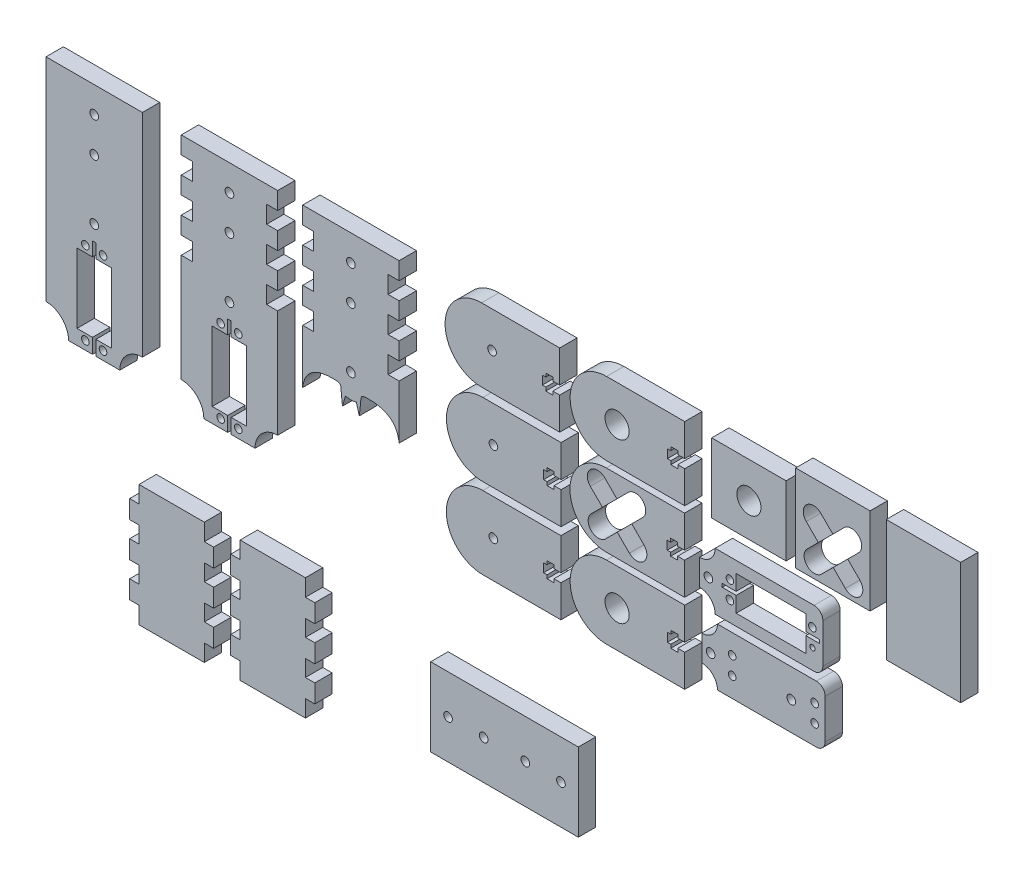
SolidWorks part; units mm, degrees
ref_plane "Front Plane" through (0, 0, 0) normal (0, 0, 1) x (1, 0, 0)
ref_plane "Top Plane" through (0, 0, 0) normal (0, 1, 0) x (1, 0, 0)
ref_plane "Right Plane" through (0, 0, 0) normal (1, 0, 0) x (0, 0, -1)
sketch "Sketch1" plane through (0, 0, 0) normal (0, 0, 1) x (1, 0, 0)
  line L0 (-3964.9917, 706.1421) -> (-3922.1917, 706.1421)
  line L1 (-3964.9917, 656.1421) -> (-3922.1917, 656.1421)
  line L2 (-3964.9917, 656.1421) -> (-3964.9917, 706.1421)
  line L3 (-3922.1917, 656.1421) -> (-3922.1917, 706.1421)
  line L4 (-3951.9356, 675.4821) -> (-3958.9122, 682.4587)
  line L5 (-3912.8317, 706.5254) -> (-3870.0317, 706.5254)
  line L6 (-3954.4311, 642.9035) -> (-4011.3511, 642.9035)
  line L7 (-3959.1812, 625.4535) -> (-3959.1812, 616.5435)
  line L8 (-3943.5917, 683.826) -> (-3950.5683, 690.8026)
  line L9 (-3935.0529, 675.677) -> (-3928.0764, 668.7004)
  line L10 (-3943.3968, 667.3332) -> (-3936.4202, 660.3566)
  line L11 (-3951.9356, 675.4821) -> (-3958.4409, 668.9767)
  line L12 (-3943.3968, 667.3332) -> (-3949.9022, 660.8278)
  line L13 (-3935.0529, 675.677) -> (-3928.7425, 681.9875)
  line L14 (-3943.5917, 683.826) -> (-3937.0863, 690.3314)
  line L15 (-4100.1427, 604.8084) -> (-4100.1427, 586.3084)
  line L16 (-4028.9793, 651.6288) -> (-4028.9793, 633.1288)
  line L17 (-3949.3511, 637.8235) -> (-3949.3511, 615.0835)
  line L18 (-3954.4311, 610.0035) -> (-4011.3511, 610.0035)
  line L19 (-4028.9793, 609.6288) -> (-4028.9793, 628.1288)
  line L20 (-3959.1812, 616.5435) -> (-3999.2812, 616.5435)
  line L21 (-3999.2812, 616.5435) -> (-3999.2812, 625.4535)
  line L22 (-3999.2812, 636.3635) -> (-3959.1812, 636.3635)
  line L23 (-3959.1812, 636.3635) -> (-3959.1812, 627.4535)
  line L24 (-4019.0444, 596.7744) -> (-4019.0444, 581.8744)
  line L25 (-4269.6074, 685.3237) -> (-4263.2574, 685.3237)
  line L26 (-4028.9793, 628.1288) -> (-4032.9793, 628.1288)
  line L27 (-4100.1427, 562.8084) -> (-4100.1427, 581.3084)
  line L28 (-4100.1427, 581.3084) -> (-4104.1427, 581.3084)
  line L29 (-4104.1427, 581.3084) -> (-4104.1427, 579.3084)
  line L30 (-4104.1427, 579.3084) -> (-4108.1427, 579.3084)
  line L31 (-4108.1427, 579.3084) -> (-4108.1427, 581.3084)
  line L32 (-4108.1427, 581.3084) -> (-4110.1427, 581.3084)
  line L33 (-4110.1427, 581.3084) -> (-4110.1427, 586.3084)
  line L34 (-4110.1427, 586.3084) -> (-4108.1427, 586.3084)
  line L35 (-4108.1427, 586.3084) -> (-4108.1427, 588.3084)
  line L36 (-4108.1427, 588.3084) -> (-4104.1427, 588.3084)
  line L37 (-4104.1427, 588.3084) -> (-4104.1427, 586.3084)
  line L38 (-4104.1427, 586.3084) -> (-4100.1427, 586.3084)
  line L39 (-4032.9793, 628.1288) -> (-4032.9793, 626.1288)
  line L40 (-4032.9793, 626.1288) -> (-4036.9793, 626.1288)
  line L41 (-4100.1427, 604.8084) -> (-4145.1427, 604.8084)
  line L42 (-4100.1427, 562.8084) -> (-4145.1427, 562.8084)
  line L43 (-4036.9793, 626.1288) -> (-4036.9793, 628.1288)
  line L44 (-4036.9793, 628.1288) -> (-4038.9793, 628.1288)
  line L45 (-4290.2684, 460.516) -> (-4290.2684, 450.016)
  line L46 (-4038.9793, 628.1288) -> (-4038.9793, 633.1288)
  line L47 (-4290.2684, 500.516) -> (-4284.8684, 500.516)
  line L48 (-4038.9793, 633.1288) -> (-4036.9793, 633.1288)
  line L49 (-4036.9793, 633.1288) -> (-4036.9793, 635.1288)
  line L50 (-4036.9793, 635.1288) -> (-4032.9793, 635.1288)
  line L51 (-4032.9793, 635.1288) -> (-4032.9793, 633.1288)
  line L52 (-4032.9793, 633.1288) -> (-4028.9793, 633.1288)
  line L53 (-4028.9793, 651.6288) -> (-4073.9793, 651.6288)
  line L54 (-4076.2632, 630.9006) -> (-4083.2397, 637.8772)
  line L55 (-4028.9793, 609.6288) -> (-4073.9793, 609.6288)
  line L56 (-4067.9193, 639.2444) -> (-4074.8959, 646.221)
  line L57 (-4059.3805, 631.0955) -> (-4052.4039, 624.1189)
  line L58 (-4067.7244, 622.7516) -> (-4060.7478, 615.775)
  line L59 (-4076.2632, 630.9006) -> (-4082.7685, 624.3952)
  line L60 (-4067.7244, 622.7516) -> (-4074.2298, 616.2462)
  line L61 (-4059.3805, 631.0955) -> (-4053.0701, 637.4059)
  line L62 (-4067.9193, 639.2444) -> (-4061.4139, 645.7498)
  line L64 (-4028.879, 605.7744) -> (-4028.879, 587.2744)
  line L65 (-4028.879, 563.7744) -> (-4028.879, 582.2744)
  line L66 (-4028.879, 582.2744) -> (-4032.879, 582.2744)
  line L67 (-4032.879, 582.2744) -> (-4032.879, 580.2744)
  line L68 (-4032.879, 580.2744) -> (-4036.879, 580.2744)
  line L69 (-4036.879, 580.2744) -> (-4036.879, 582.2744)
  line L70 (-4036.879, 582.2744) -> (-4038.879, 582.2744)
  line L71 (-4013.3471, 696.9694) -> (-3970.5471, 696.9694)
  line L72 (-4013.3471, 656.9694) -> (-3970.5471, 656.9694)
  line L73 (-4013.3471, 656.9694) -> (-4013.3471, 696.9694)
  line L74 (-3970.5471, 656.9694) -> (-3970.5471, 696.9694)
  line L75 (-4038.879, 582.2744) -> (-4038.879, 587.2744)
  line L76 (-4038.879, 587.2744) -> (-4036.879, 587.2744)
  line L77 (-4036.879, 587.2744) -> (-4036.879, 589.2744)
  line L78 (-4036.879, 589.2744) -> (-4032.879, 589.2744)
  line L79 (-4032.879, 589.2744) -> (-4032.879, 587.2744)
  line L80 (-4032.879, 587.2744) -> (-4028.879, 587.2744)
  line L81 (-4028.879, 605.7744) -> (-4073.879, 605.7744)
  line L82 (-4028.879, 697.3237) -> (-4028.879, 678.8237)
  line L83 (-4028.879, 563.7744) -> (-4073.879, 563.7744)
  line L84 (-4028.879, 655.3237) -> (-4028.879, 673.8237)
  line L85 (-4028.879, 673.8237) -> (-4032.879, 673.8237)
  line L86 (-4032.879, 673.8237) -> (-4032.879, 671.8237)
  line L87 (-4032.879, 671.8237) -> (-4036.879, 671.8237)
  line L88 (-4036.879, 671.8237) -> (-4036.879, 673.8237)
  line L89 (-4036.879, 673.8237) -> (-4038.879, 673.8237)
  line L90 (-3912.8317, 636.5254) -> (-3870.0317, 636.5254)
  line L91 (-3912.8317, 636.5254) -> (-3912.8317, 706.5254)
  line L92 (-3870.0317, 636.5254) -> (-3870.0317, 706.5254)
  line L93 (-4038.879, 673.8237) -> (-4038.879, 678.8237)
  line L94 (-4038.879, 678.8237) -> (-4036.879, 678.8237)
  line L95 (-4036.879, 678.8237) -> (-4036.879, 680.8237)
  line L96 (-4036.879, 680.8237) -> (-4032.879, 680.8237)
  line L97 (-4032.879, 680.8237) -> (-4032.879, 678.8237)
  line L98 (-4032.879, 678.8237) -> (-4028.879, 678.8237)
  line L99 (-4028.879, 697.3237) -> (-4073.879, 697.3237)
  line L100 (-4028.879, 655.3237) -> (-4073.879, 655.3237)
  line L101 (-4100.8598, 698.0366) -> (-4100.8598, 679.5366)
  line L102 (-4100.8598, 656.0366) -> (-4100.8598, 674.5366)
  line L103 (-4100.8598, 674.5366) -> (-4104.8598, 674.5366)
  line L104 (-4104.8598, 674.5366) -> (-4104.8598, 672.5366)
  line L105 (-4104.8598, 672.5366) -> (-4108.8598, 672.5366)
  line L106 (-4108.8598, 672.5366) -> (-4108.8598, 674.5366)
  line L107 (-4108.8598, 674.5366) -> (-4110.8598, 674.5366)
  line L108 (-4110.8598, 674.5366) -> (-4110.8598, 679.5366)
  line L109 (-4110.8598, 679.5366) -> (-4108.8598, 679.5366)
  line L110 (-4108.8598, 679.5366) -> (-4108.8598, 681.5366)
  line L111 (-4108.8598, 681.5366) -> (-4104.8598, 681.5366)
  line L112 (-4104.8598, 681.5366) -> (-4104.8598, 679.5366)
  line L113 (-4104.8598, 679.5366) -> (-4100.8598, 679.5366)
  line L114 (-4100.8598, 698.0366) -> (-4145.8598, 698.0366)
  line L115 (-4100.8598, 656.0366) -> (-4145.8598, 656.0366)
  line L116 (-3953.1244, 605.7744) -> (-4010.0444, 605.7744)
  line L117 (-3948.0444, 577.9544) -> (-3948.0444, 600.6944)
  line L118 (-3953.1244, 572.8744) -> (-4010.0444, 572.8744)
  line L119 (-4100.0853, 651.2486) -> (-4100.0853, 632.7486)
  line L120 (-4020.3511, 619.0035) -> (-4020.3511, 633.9035)
  line L121 (-4100.0853, 609.2486) -> (-4100.0853, 627.7486)
  line L122 (-4100.0853, 627.7486) -> (-4104.0853, 627.7486)
  line L123 (-4104.0853, 627.7486) -> (-4104.0853, 625.7486)
  line L124 (-4104.0853, 625.7486) -> (-4108.0853, 625.7486)
  line L125 (-4108.0853, 625.7486) -> (-4108.0853, 627.7486)
  line L126 (-4108.0853, 627.7486) -> (-4110.0853, 627.7486)
  line L127 (-4110.0853, 627.7486) -> (-4110.0853, 632.7486)
  line L128 (-4110.0853, 632.7486) -> (-4108.0853, 632.7486)
  line L129 (-4108.0853, 632.7486) -> (-4108.0853, 634.7486)
  line L130 (-4108.0853, 634.7486) -> (-4104.0853, 634.7486)
  line L131 (-4104.0853, 634.7486) -> (-4104.0853, 632.7486)
  line L132 (-4104.0853, 632.7486) -> (-4100.0853, 632.7486)
  line L133 (-4100.0853, 651.2486) -> (-4145.0853, 651.2486)
  line L134 (-4100.0853, 609.2486) -> (-4145.0853, 609.2486)
  line L135 (-4290.2684, 450.016) -> (-4284.8684, 450.016)
  line L136 (-4290.2684, 460.516) -> (-4284.8684, 460.516)
  line L137 (-4284.8684, 440.266) -> (-4247.2684, 440.266)
  line L138 (-4284.8684, 460.516) -> (-4284.8684, 470.016)
  line L139 (-4284.8684, 470.016) -> (-4290.2684, 470.016)
  line L140 (-4284.8684, 480.516) -> (-4290.2684, 480.516)
  line L141 (-4284.8684, 480.516) -> (-4284.8684, 490.016)
  line L142 (-4290.2684, 490.016) -> (-4284.8684, 490.016)
  line L143 (-4290.2684, 470.016) -> (-4290.2684, 480.516)
  line L144 (-4290.2684, 490.016) -> (-4290.2684, 500.516)
  line L145 (-4284.8684, 500.516) -> (-4284.8684, 510.266)
  line L146 (-4284.8684, 510.266) -> (-4247.2684, 510.266)
  line L147 (-4284.8684, 450.016) -> (-4284.8684, 440.266)
  line L148 (-4247.2684, 450.016) -> (-4247.2684, 440.266)
  line L149 (-4247.2684, 500.516) -> (-4247.2684, 510.266)
  line L150 (-4241.8684, 490.016) -> (-4241.8684, 500.516)
  line L151 (-4241.8684, 470.016) -> (-4241.8684, 480.516)
  line L152 (-4241.8684, 490.016) -> (-4247.2684, 490.016)
  line L153 (-4247.2684, 480.516) -> (-4247.2684, 490.016)
  line L154 (-4247.2684, 480.516) -> (-4241.8684, 480.516)
  line L155 (-4247.2684, 470.016) -> (-4241.8684, 470.016)
  line L156 (-4247.2684, 460.516) -> (-4247.2684, 470.016)
  line L157 (-4241.8684, 460.516) -> (-4247.2684, 460.516)
  line L158 (-4241.8684, 450.016) -> (-4247.2684, 450.016)
  line L159 (-4241.8684, 500.516) -> (-4247.2684, 500.516)
  line L160 (-4241.8684, 460.516) -> (-4241.8684, 450.016)
  line L161 (-4281.0974, 608.9237) -> (-4281.0974, 568.8237)
  line L162 (-4281.0974, 568.8237) -> (-4290.0074, 568.8237)
  line L163 (-4300.9174, 568.8237) -> (-4300.9174, 608.9237)
  line L164 (-4300.9174, 608.9237) -> (-4292.0074, 608.9237)
  line L165 (-4396.6234, 695.3237) -> (-4396.6234, 573.3237)
  line L166 (-4263.2574, 685.3237) -> (-4263.2574, 695.3237)
  line L167 (-4341.1234, 695.3237) -> (-4341.1234, 573.3237)
  line L168 (-4530.5914, 378.0464) -> (-4530.5914, 375.7196) construction
  line L169 (-3959.1812, 627.4535) -> (-3951.3511, 627.4535)
  line L170 (-3999.2812, 627.4535) -> (-4007.2812, 627.4535)
  line L171 (-4312.4074, 685.3237) -> (-4318.7574, 685.3237)
  line L172 (0.7395, 0.0077) -> (1.404, 0.54)
  line L173 (-0.7338, 0.0079) -> (-1.3931, 0.5675)
  line L174 (0.4061, 0.6361) -> (0.2373, 1.4283)
  line L175 (0.4061, 0.6361) -> (1.2054, 0.8987)
  line L176 (-0.3925, 0.6096) -> (-1.1875, 0.9222)
  line L177 (-0.3925, 0.6096) -> (-0.2029, 1.4364)
  line L178 (0.7393, -0.0078) -> (1.3933, -0.5526)
  line L179 (0.3955, -0.6325) -> (1.2054, -0.997)
  line L180 (-2.702, -2.3323) -> (2.8673, -2.3323)
  line L181 (2.8673, 2.2092) -> (2.8673, -2.3323)
  line L182 (0.3955, -0.6325) -> (0.2134, -1.5425)
  line L183 (-0.4078, -0.6246) -> (-0.227, -1.5139)
  line L184 (-0.7338, 0.0079) -> (-1.4039, -0.525)
  line L185 (-0.4078, -0.6246) -> (-1.1875, -0.9186)
  line L186 (0.6417, 0.0734) -> (0.486, 0.2032)
  line L187 (0.6403, -0.0717) -> (0.4821, -0.1985)
  line L188 (-0.2029, 1.4364) -> (-0.0986, 1.6207)
  line L189 (-0.0986, 1.6207) -> (0.0096, 1.6807)
  line L190 (0.0096, 1.6807) -> (0.1215, 1.6166)
  line L191 (0.1215, 1.6166) -> (0.2373, 1.4283)
  line L192 (1.2054, -0.997) -> (1.3895, -0.7778)
  line L193 (1.3895, -0.7778) -> (1.3933, -0.5526)
  line L194 (-0.227, -1.5139) -> (-0.1073, -1.6522)
  line L195 (-0.1073, -1.6522) -> (0.0152, -1.6892)
  line L196 (0.0152, -1.6892) -> (0.2134, -1.5425)
  line L197 (-2.702, 2.2092) -> (2.8673, 2.2092)
  line L198 (-2.702, 2.2092) -> (-2.702, -2.3323)
  line L199 (1.2054, 0.8987) -> (1.4123, 0.7492)
  line L200 (1.4123, 0.7492) -> (1.404, 0.54)
  line L201 (-1.1875, 0.9222) -> (-1.3973, 0.7769)
  line L202 (-1.3973, 0.7769) -> (-1.3931, 0.5675)
  line L203 (-1.1875, -0.9186) -> (-1.4064, -0.7464)
  line L204 (-1.4064, -0.7464) -> (-1.4039, -0.525)
  line L205 (0.7395, 0.0077) -> (1.404, 0.54)
  line L206 (-0.7338, 0.0079) -> (-1.3931, 0.5675)
  line L207 (0.4061, 0.6361) -> (0.2373, 1.4283)
  line L208 (0.4061, 0.6361) -> (1.2054, 0.8987)
  line L209 (-0.3925, 0.6096) -> (-1.1875, 0.9222)
  line L210 (-0.3925, 0.6096) -> (-0.2029, 1.4364)
  line L211 (0.7393, -0.0078) -> (1.3933, -0.5526)
  line L212 (0.3955, -0.6325) -> (1.2054, -0.997)
  line L213 (-2.702, -2.3323) -> (2.8673, -2.3323)
  line L214 (2.8673, 2.2092) -> (2.8673, -2.3323)
  line L215 (0.3955, -0.6325) -> (0.2134, -1.5425)
  line L216 (-0.4078, -0.6246) -> (-0.227, -1.5139)
  line L217 (-0.7338, 0.0079) -> (-1.4039, -0.525)
  line L218 (-0.4078, -0.6246) -> (-1.1875, -0.9186)
  line L219 (0.6417, 0.0734) -> (0.486, 0.2032)
  line L220 (0.6403, -0.0717) -> (0.4821, -0.1985)
  line L221 (-0.2029, 1.4364) -> (-0.0986, 1.6207)
  line L222 (-0.0986, 1.6207) -> (0.0096, 1.6807)
  line L223 (0.0096, 1.6807) -> (0.1215, 1.6166)
  line L224 (0.1215, 1.6166) -> (0.2373, 1.4283)
  line L225 (1.2054, -0.997) -> (1.3895, -0.7778)
  line L226 (1.3895, -0.7778) -> (1.3933, -0.5526)
  line L227 (-0.227, -1.5139) -> (-0.1073, -1.6522)
  line L228 (-0.1073, -1.6522) -> (0.0152, -1.6892)
  line L229 (0.0152, -1.6892) -> (0.2134, -1.5425)
  line L230 (-2.702, 2.2092) -> (2.8673, 2.2092)
  line L231 (-2.702, 2.2092) -> (-2.702, -2.3323)
  line L232 (1.2054, 0.8987) -> (1.4123, 0.7492)
  line L233 (1.4123, 0.7492) -> (1.404, 0.54)
  line L234 (-1.1875, 0.9222) -> (-1.3973, 0.7769)
  line L235 (-1.3973, 0.7769) -> (-1.3931, 0.5675)
  line L236 (-1.1875, -0.9186) -> (-1.4064, -0.7464)
  line L237 (-1.4064, -0.7464) -> (-1.4039, -0.525)
  line L238 (-3959.1812, 625.4535) -> (-3951.3511, 625.4535)
  line L239 (-4007.2812, 627.4535) -> (-4007.2812, 625.4535)
  line L240 (-4007.2812, 625.4535) -> (-3999.2812, 625.4535)
  line L241 (-3999.2812, 627.4535) -> (-3999.2812, 636.3635)
  line L242 (-4530.5914, 378.0464) -> (-4533.4939, 378.0464) construction
  line L243 (-4292.0074, 560.3237) -> (-4305.7574, 560.3237)
  line L244 (-4175.1427, 504.4282) -> (-4175.1427, 459.4282)
  line L245 (-3951.3511, 627.4535) -> (-3951.3511, 625.4535)
  line L246 (-4090.1427, 504.4282) -> (-4090.1427, 459.4282)
  line L247 (-4292.0074, 616.9237) -> (-4290.0074, 616.9237)
  line L248 (-4401.922, 786.8661) -> (-4409.4671, 786.8661) construction
  line L249 (-4290.0074, 616.9237) -> (-4290.0074, 608.9237)
  line L250 (-4290.0074, 568.8237) -> (-4290.0074, 560.3237)
  line L251 (-4292.0074, 568.8237) -> (-4292.0074, 560.3237)
  line L252 (-4292.0074, 568.8237) -> (-4300.9174, 568.8237)
  line L253 (-4540.4409, 376.8464) -> (-4520.7419, 376.8464)
  line L254 (-4292.0074, 616.9237) -> (-4292.0074, 608.9237)
  line L255 (-4290.0074, 608.9237) -> (-4281.0974, 608.9237)
  line L256 (-4515.5441, 376.4214) -> (-4515.5441, 379.6714)
  line L257 (-4401.922, 784.8687) -> (-4401.922, 788.8459) construction
  line L258 (-4411.7715, 785.6661) -> (-4392.0725, 785.6661)
  line L260 (-4386.422, 792.1599) -> (-4386.422, 786.7278) construction
  line L261 (-4386.422, 785.6661) -> (-4386.422, 788.0661)
  line L262 (-4416.1645, 785.2411) -> (-4416.1645, 788.4911)
  line L263 (-4383.6234, 560.3237) -> (-4369.8734, 560.3237)
  line L264 (-4386.422, 785.2411) -> (-4386.422, 788.4911)
  line L265 (-4411.7715, 788.0661) -> (-4392.0725, 788.0661)
  line L266 (-4341.1234, 695.3237) -> (-4396.6234, 695.3237)
  line L267 (-4545.6388, 376.4214) -> (-4545.6388, 379.6714)
  line L268 (-4369.8734, 608.9237) -> (-4378.7834, 608.9237)
  line L269 (-4367.8734, 616.9237) -> (-4367.8734, 608.9237)
  line L270 (-4367.8734, 568.8237) -> (-4358.9634, 568.8237)
  line L271 (-4367.8734, 568.8237) -> (-4367.8734, 560.3237)
  line L272 (-4369.8734, 568.8237) -> (-4369.8734, 560.3237)
  line L273 (-4369.8734, 616.9237) -> (-4369.8734, 608.9237)
  line L274 (-4367.8734, 616.9237) -> (-4369.8734, 616.9237)
  line L275 (-4367.8734, 560.3237) -> (-4354.1234, 560.3237)
  line L276 (-4530.8384, 389.3722) -> (-4530.8384, 387.0454) construction
  line L277 (-4530.8384, 389.3722) -> (-4533.7408, 389.3722) construction
  line L278 (-4358.9634, 608.9237) -> (-4367.8734, 608.9237)
  line L279 (-4358.9634, 568.8237) -> (-4358.9634, 608.9237)
  line L280 (-4378.7834, 568.8237) -> (-4369.8734, 568.8237)
  line L281 (-4378.7834, 608.9237) -> (-4378.7834, 568.8237)
  line L283 (-4540.6879, 388.1722) -> (-4520.9889, 388.1722)
  line L284 (-4516.5959, 387.7472) -> (-4516.5959, 390.9972)
  line L285 (-4224.2086, 612.4687) -> (-4225.9192, 606.4797)
  line L287 (-4255.7871, 785.1807) -> (-4243.7871, 785.1807)
  line L288 (-4265.6366, 786.3807) -> (-4271.2871, 786.8057)
  line L289 (-4271.2871, 789.5994) -> (-4271.2871, 784.1674) construction
  line L290 (-4271.2871, 783.9807) -> (-4240.2871, 783.9807)
  line L291 (-4240.2871, 790.4745) -> (-4240.2871, 785.0425) construction
  line L292 (-4271.2871, 783.9807) -> (-4271.2871, 786.3807)
  line L293 (-4271.2871, 786.3807) -> (-4240.2871, 786.3807)
  line L294 (-4240.2871, 783.9807) -> (-4240.2871, 786.3807)
  line L295 (-4271.2871, 783.9807) -> (-4240.2871, 786.3807) construction
  line L296 (-4271.2871, 783.961) -> (-4240.2871, 786.4004) construction
  line L297 (-4271.2871, 786.4004) -> (-4240.2871, 783.961) construction
  line L298 (-4255.7871, 785.1807) -> (-4267.7871, 785.1807)
  line L299 (-4267.7871, 785.1807) -> (-4271.2871, 785.1807)
  line L300 (-4243.7871, 785.1807) -> (-4240.2871, 785.1807)
  line L301 (-4271.2871, 786.3807) -> (-4240.2871, 783.9807) construction
  line L302 (-4271.2871, 783.5557) -> (-4240.2871, 783.5557)
  line L303 (-4271.2871, 783.5557) -> (-4271.2871, 786.8057)
  line L304 (-4271.2871, 786.8057) -> (-4240.2871, 786.8057)
  line L305 (-4240.2871, 783.5557) -> (-4240.2871, 786.8057)
  line L306 (-4271.2871, 783.5557) -> (-4240.2871, 786.8057) construction
  line L307 (-4271.2871, 786.8057) -> (-4240.2871, 783.5557) construction
  line L309 (-4217.9443, 612.4687) -> (-4216.2337, 606.4797)
  line L310 (-4545.0808, 387.7472) -> (-4545.0808, 390.9972)
  line L311 (-4540.6879, 390.5722) -> (-4520.9889, 390.5722)
  line L314 (-4540.4409, 379.2464) -> (-4520.7419, 379.2464)
  line L361 (-4348.4847, 459.1217) -> (-4348.4847, 448.6217)
  line L368 (-4175.1427, 504.4282) -> (-4090.1427, 504.4282)
  line L370 (-4175.1427, 459.4282) -> (-4090.1427, 459.4282)
  line L371 (-4193.3264, 675.3237) -> (-4199.6764, 675.3237)
  line L372 (-4318.7574, 685.3237) -> (-4318.7574, 695.3237)
  line L374 (-4318.7574, 695.3237) -> (-4263.2574, 695.3237)
  line L381 (-4193.3264, 665.3237) -> (-4193.3264, 675.3237)
  line L382 (-4199.6764, 665.3237) -> (-4193.3264, 665.3237)
  line L386 (-4193.3264, 655.3237) -> (-4199.6764, 655.3237)
  line L387 (-4199.6764, 665.3237) -> (-4199.6764, 655.3237)
  line L391 (-4263.2574, 635.3237) -> (-4263.2574, 573.3237)
  line L392 (-4199.6764, 685.3237) -> (-4199.6764, 675.3237)
  line L393 (-4318.7574, 573.3237) -> (-4318.7574, 635.3237)
  line L394 (-4276.2574, 560.3237) -> (-4290.0074, 560.3237)
  line L395 (-4269.6074, 685.3237) -> (-4269.6074, 675.3237)
  line L396 (-4269.6074, 645.3237) -> (-4269.6074, 635.3237)
  line L397 (-4269.6074, 665.3237) -> (-4269.6074, 655.3237)
  line L398 (-4269.6074, 645.3237) -> (-4263.2574, 645.3237)
  line L399 (-4269.6074, 635.3237) -> (-4263.2574, 635.3237)
  line L400 (-4263.2574, 645.3237) -> (-4263.2574, 655.3237)
  line L401 (-4312.4074, 635.3237) -> (-4318.7574, 635.3237)
  line L402 (-4263.2574, 655.3237) -> (-4269.6074, 655.3237)
  line L403 (-4199.6764, 645.3237) -> (-4193.3264, 645.3237)
  line L404 (-4269.6074, 665.3237) -> (-4263.2574, 665.3237)
  line L405 (-4263.2574, 665.3237) -> (-4263.2574, 675.3237)
  line L406 (-4263.2574, 675.3237) -> (-4269.6074, 675.3237)
  line L407 (-4312.4074, 635.3237) -> (-4318.7574, 635.3237)
  line L408 (-4193.3264, 645.3237) -> (-4193.3264, 655.3237)
  line L409 (-4312.4074, 645.3237) -> (-4312.4074, 635.3237)
  line L410 (-4318.7574, 645.3237) -> (-4318.7574, 655.3237)
  line L411 (-4312.4074, 645.3237) -> (-4318.7574, 645.3237)
  line L412 (-4312.4074, 685.3237) -> (-4312.4074, 675.3237)
  line L413 (-4312.4074, 665.3237) -> (-4312.4074, 655.3237)
  line L414 (-4318.7574, 655.3237) -> (-4312.4074, 655.3237)
  line L415 (-4312.4074, 665.3237) -> (-4318.7574, 665.3237)
  line L416 (-4318.7574, 665.3237) -> (-4318.7574, 675.3237)
  line L417 (-4318.7574, 675.3237) -> (-4312.4074, 675.3237)
  line L418 (-4199.6764, 645.3237) -> (-4199.6764, 635.3237)
  line L419 (-4199.6764, 635.3237) -> (-4193.3264, 635.3237)
  line L420 (-4248.8264, 675.3237) -> (-4242.4764, 675.3237)
  line L421 (-4248.8264, 665.3237) -> (-4248.8264, 675.3237)
  line L422 (-4242.4764, 665.3237) -> (-4248.8264, 665.3237)
  line L423 (-4248.8264, 655.3237) -> (-4242.4764, 655.3237)
  line L424 (-4199.6764, 635.3237) -> (-4193.3264, 635.3237)
  line L425 (-4248.8264, 645.3237) -> (-4248.8264, 655.3237)
  line L426 (-4242.4764, 635.3237) -> (-4248.8264, 635.3237)
  line L427 (-4242.4764, 645.3237) -> (-4248.8264, 645.3237)
  line L428 (-4242.4764, 665.3237) -> (-4242.4764, 655.3237)
  line L429 (-4242.4764, 645.3237) -> (-4242.4764, 635.3237)
  line L430 (-4242.4764, 685.3237) -> (-4242.4764, 675.3237)
  line L432 (-4193.3264, 604.3237) -> (-4193.3264, 635.3237)
  line L433 (-4248.8264, 635.3237) -> (-4248.8264, 604.3237)
  line L434 (-4348.4847, 499.1217) -> (-4343.0847, 499.1217)
  line L435 (-4348.4847, 448.6217) -> (-4343.0847, 448.6217)
  line L436 (-4348.4847, 459.1217) -> (-4343.0847, 459.1217)
  line L437 (-4193.3264, 695.3237) -> (-4248.8264, 695.3237)
  line L438 (-4193.3264, 685.3237) -> (-4193.3264, 695.3237)
  line L440 (-4199.6764, 685.3237) -> (-4193.3264, 685.3237)
  line L441 (-4248.8264, 685.3237) -> (-4248.8264, 695.3237)
  line L442 (-4242.4764, 685.3237) -> (-4248.8264, 685.3237)
  line L443 (-4343.0847, 438.8717) -> (-4305.4847, 438.8717)
  line L444 (-4343.0847, 459.1217) -> (-4343.0847, 468.6217)
  line L445 (-4343.0847, 468.6217) -> (-4348.4847, 468.6217)
  line L446 (-4343.0847, 479.1217) -> (-4348.4847, 479.1217)
  line L447 (-4343.0847, 479.1217) -> (-4343.0847, 488.6217)
  line L448 (-4348.4847, 488.6217) -> (-4343.0847, 488.6217)
  line L449 (-4348.4847, 468.6217) -> (-4348.4847, 479.1217)
  line L450 (-4348.4847, 488.6217) -> (-4348.4847, 499.1217)
  line L451 (-4343.0847, 499.1217) -> (-4343.0847, 508.8717)
  line L452 (-4343.0847, 508.8717) -> (-4305.4847, 508.8717)
  line L453 (-4343.0847, 448.6217) -> (-4343.0847, 438.8717)
  line L455 (-4305.4847, 448.6217) -> (-4305.4847, 438.8717)
  line L456 (-4305.4847, 499.1217) -> (-4305.4847, 508.8717)
  line L457 (-4300.0847, 488.6217) -> (-4300.0847, 499.1217)
  line L458 (-4300.0847, 468.6217) -> (-4300.0847, 479.1217)
  line L459 (-4300.0847, 488.6217) -> (-4305.4847, 488.6217)
  line L460 (-4305.4847, 479.1217) -> (-4305.4847, 488.6217)
  line L461 (-4305.4847, 479.1217) -> (-4300.0847, 479.1217)
  line L462 (-4305.4847, 468.6217) -> (-4300.0847, 468.6217)
  line L463 (-4305.4847, 459.1217) -> (-4305.4847, 468.6217)
  line L465 (-4300.0847, 459.1217) -> (-4305.4847, 459.1217)
  line L466 (-4300.0847, 448.6217) -> (-4305.4847, 448.6217)
  line L467 (-4300.0847, 499.1217) -> (-4305.4847, 499.1217)
  line L468 (-4300.0847, 459.1217) -> (-4300.0847, 448.6217)
  arc A0 (-4019.0444, 581.8744) -> (-4010.0444, 572.8744) centre (-4019.0444, 572.8744) cw
  circle A1 centre (-4067.9193, 630.9006) radius 3.5
  arc A2 (-4010.0444, 605.7744) -> (-4019.0444, 596.7744) centre (-4019.0444, 605.7744) cw
  circle A3 centre (-4002.8712, 621.3685) radius 2.19
  circle A4 centre (-4002.8712, 631.5385) radius 2.19
  circle A5 centre (-3955.3712, 631.5385) radius 2.19
  circle A6 centre (-4015.2695, 626.4535) radius 2.5
  arc A7 (-3949.3511, 615.0835) -> (-3954.4311, 610.0035) centre (-3954.4311, 615.0835) cw
  arc A8 (-3954.4311, 642.9035) -> (-3949.3511, 637.8235) centre (-3954.4311, 637.8235) cw
  circle A9 centre (-3954.0646, 594.4094) radius 2.19
  circle A10 centre (-3943.5917, 675.4821) radius 3.5
  arc A11 (-3958.9122, 682.4587) -> (-3950.5683, 690.8026) centre (-3954.7402, 686.6306) cw
  arc A12 (-3958.4409, 668.9767) -> (-3949.9022, 660.8278) centre (-3954.2667, 664.8025) ccw
  arc A13 (-3936.4202, 660.3566) -> (-3928.0764, 668.7004) centre (-3932.2483, 664.5285) ccw
  arc A14 (-3928.7425, 681.9875) -> (-3937.0863, 690.3314) centre (-3932.9144, 686.1594) ccw
  arc A15 (-4073.9793, 609.6288) -> (-4073.9793, 651.6288) centre (-4073.9793, 630.6288) cw
  arc A16 (-4083.2397, 637.8772) -> (-4074.8959, 646.221) centre (-4079.0678, 642.0491) cw
  circle A17 centre (-4139.0827, 584.0802) radius 2.5
  arc A18 (-4145.1427, 562.8084) -> (-4145.1427, 604.8084) centre (-4145.1427, 583.8084) cw
  arc A19 (-4082.7685, 624.3952) -> (-4074.2298, 616.2462) centre (-4078.5943, 620.221) ccw
  arc A20 (-4060.7478, 615.775) -> (-4052.4039, 624.1189) centre (-4056.5759, 619.9469) ccw
  arc A21 (-4053.0701, 637.4059) -> (-4061.4139, 645.7498) centre (-4057.242, 641.5779) ccw
  circle A22 centre (-3991.9471, 676.3094) radius 6.95
  circle A23 centre (-4067.819, 584.7744) radius 6.95
  arc A24 (-4073.879, 563.7744) -> (-4073.879, 605.7744) centre (-4073.879, 584.7744) cw
  circle A25 centre (-3955.3712, 621.3685) radius 1.5
  arc A26 (-4011.3511, 610.0035) -> (-4020.3511, 619.0035) centre (-4020.3511, 610.0035) ccw
  arc A27 (-4020.3511, 633.9035) -> (-4011.3511, 642.9035) centre (-4020.3511, 642.9035) ccw
  circle A28 centre (-4139.0253, 630.5204) radius 2.5
  arc A29 (-4145.0853, 609.2486) -> (-4145.0853, 651.2486) centre (-4145.0853, 630.2486) cw
  circle A30 centre (-4139.7998, 677.3084) radius 2.5
  arc A31 (-4145.8598, 656.0366) -> (-4145.8598, 698.0366) centre (-4145.8598, 677.0366) cw
  arc A32 (-3953.1244, 572.8744) -> (-3948.0444, 577.9544) centre (-3953.1244, 577.9544) ccw
  arc A33 (-3948.0444, 600.6944) -> (-3953.1244, 605.7744) centre (-3953.1244, 600.6944) ccw
  circle A34 centre (-4013.9628, 589.3244) radius 2.5
  circle A35 centre (-3954.0646, 584.2394) radius 2.19
  circle A36 centre (-4067.819, 676.3237) radius 6.95
  arc A37 (-4073.879, 655.3237) -> (-4073.879, 697.3237) centre (-4073.879, 676.3237) cw
  circle A38 centre (-4001.5646, 584.2394) radius 2.19
  circle A39 centre (-4001.5646, 594.4094) radius 2.19
  circle A40 centre (-3967.5346, 589.3244) radius 2.5
  circle A41 centre (-4285.9224, 565.2337) radius 2.19
  circle A42 centre (-4296.0924, 565.2337) radius 2.19
  circle A43 centre (-4296.0924, 612.7337) radius 2.19
  circle A44 centre (-4285.9224, 612.7337) radius 2.19
  circle A45 centre (-4368.8734, 660.3237) radius 2.5
  circle A46 centre (-4368.8734, 625.8237) radius 2.5
  circle A47 centre (-4368.8734, 680.3237) radius 2.5
  circle A48 centre (-4373.9584, 612.7337) radius 2.19
  circle A49 centre (-4363.7884, 612.7337) radius 2.19
  circle A50 centre (-4363.7884, 565.2337) radius 2.19
  circle A51 centre (-4373.9584, 565.2337) radius 2.19
  arc A52 (-4305.7574, 560.3237) -> (-4318.7574, 573.3237) centre (-4318.7574, 560.3237) ccw
  arc A53 (-4276.2574, 560.3237) -> (-4263.2574, 573.3237) centre (-4263.2574, 560.3237) cw
  arc A54 (-4383.6234, 560.3237) -> (-4396.6234, 573.3237) centre (-4396.6234, 560.3237) ccw
  arc A55 (-4341.1234, 573.3237) -> (-4354.1234, 560.3237) centre (-4341.1234, 560.3237) ccw
  circle A56 centre (-4542.8384, 389.3722) radius 1.5
  circle A57 centre (-4518.8384, 389.3722) radius 1.5
  circle A58 centre (-4144.6427, 481.9282) radius 2.5
  circle A59 centre (-4120.6427, 481.9282) radius 2.5
  circle A60 centre (-4542.5914, 378.0464) radius 1.5
  circle A61 centre (-4518.5914, 378.0464) radius 1.5
  circle A62 centre (-4267.7871, 785.1807) radius 1.5
  circle A63 centre (-4243.7871, 785.1807) radius 1.5
  circle A64 centre (-4413.922, 786.8661) radius 1.5
  circle A65 centre (-4389.922, 786.8661) radius 1.5
  arc A74 (0.7395, 0.0077) -> (0.7393, -0.0078) centre (0.7457, -0.0002) ccw
  arc A75 (-0.0783, 1.7836) -> (-0.0778, 1.7832) centre (0.048, 1.9764) ccw
  arc A76 (0.7395, 0.0077) -> (0.7393, -0.0078) centre (0.7457, -0.0002) ccw
  arc A77 (-0.0783, 1.7836) -> (-0.0778, 1.7832) centre (0.048, 1.9764) ccw
  circle A78 centre (-4165.1427, 481.9282) radius 2.5
  circle A79 centre (-4100.1427, 481.9282) radius 2.5
  circle A88 centre (-4221.0764, 660.3237) radius 2.5
  circle A94 centre (-4221.0764, 625.8237) radius 2.5
  circle A96 centre (-4221.0764, 680.3237) radius 2.5
  circle A105 centre (-4291.0074, 680.3237) radius 2.5
  circle A106 centre (-4291.0074, 625.8237) radius 2.5
  circle A111 centre (-4291.0074, 660.3237) radius 2.5
  spline S0 degree 2 poles (-4545.6388, 376.4214) (-4542.288, 373.9787) (-4540.4409, 376.8464) knots 0 0 0 1 1 1
  spline S1 degree 2 poles (-4545.6388, 379.6714) (-4542.288, 382.114) (-4540.4409, 379.2464) knots 0 0 0 1 1 1
  spline S2 degree 2 poles (-4240.4756, 788.3164) (-4240.3797, 788.3203) (-4240.2871, 788.3241) knots 0 0 0 0.016615 0.016615 0.016615
  spline S3 degree 3 poles (-4265.6366, 786.3807) (-4267.634, 786.971) (-4270.7507, 787.032) (-4271.3335, 786.8009) (-4271.4299, 786.6996) knots 0 0 0 0 0.828806 1 1 1 1
  spline S4 degree 2 poles (-4386.6105, 790.0018) (-4386.5146, 790.0057) (-4386.422, 790.0094) knots 0 0 0 0.016615 0.016615 0.016615
  spline S5 degree 2 poles (-4515.5441, 376.4214) (-4518.8948, 373.9787) (-4520.7419, 376.8464) knots 0 0 0 1 1 1
  spline S6 degree 2 poles (-4515.5441, 379.6714) (-4518.8948, 382.114) (-4520.7419, 379.2464) knots 0 0 0 1 1 1
  spline S7 degree 3 poles (-4411.7715, 788.0661) (-4413.7568, 789.0538) (-4415.5213, 788.7284) (-4416.1645, 788.4911) knots 0 0 0 0 0.920896 0.920896 0.920896 0.920896
  spline S8 degree 3 poles (-4392.0725, 785.6661) (-4390.0751, 785.0758) (-4386.9584, 785.0148) (-4386.3756, 785.2459) (-4386.2792, 785.3472) knots 0 0 0 0 0.828806 1 1 1 1
  spline S9 degree 3 poles (-4392.0725, 788.0661) (-4390.2858, 788.955) (-4388.8546, 788.7465) (-4387.638, 788.4927) (-4387.6089, 788.4479) (-4386.2792, 788.3849) knots 0 0 0 0 0.828806 0.928806 1 1 1 1
  spline S10 degree 3 poles (-4520.9889, 388.1722) (-4520.287, 386.0688) (-4517.1583, 386.5566) (-4516.5959, 387.7472) knots 0 0 0 0 0.920896 0.920896 0.920896 0.920896
  spline S11 degree 3 poles (-4540.6879, 390.5722) (-4541.3898, 392.6755) (-4544.5185, 392.1878) (-4545.0808, 390.9972) knots 0 0 0 0 0.920896 0.920896 0.920896 0.920896
  spline S12 degree 3 poles (-4520.9889, 390.5722) (-4520.287, 392.6755) (-4517.1583, 392.1878) (-4516.5959, 390.9972) knots 0 0 0 0 0.920896 0.920896 0.920896 0.920896
  spline S13 degree 3 poles (-4540.6879, 388.1722) (-4541.3898, 386.0688) (-4544.5185, 386.5566) (-4545.0808, 387.7472) knots 0 0 0 0 0.920896 0.920896 0.920896 0.920896
  spline S25 degree 2 poles (-4221.0764, 611.9891) (-4222.5172, 611.995) (-4224.2086, 612.4687) knots 0 0 0 1 1 1
  spline S26 degree 2 poles (-4229.7917, 617.5158) (-4247.2883, 618.1823) (-4248.8264, 604.3237) knots 0 0 0 1 1 1
  spline S29 degree 3 poles (-4225.9192, 606.4797) (-4227.4215, 615.5449) (-4225.4179, 617.344) (-4229.7917, 617.5158) knots 0 0 0 0 1 1 1 1
  spline S32 degree 2 poles (-4221.0764, 611.9891) (-4219.6357, 611.995) (-4217.9443, 612.4687) knots 0 0 0 1 1 1
  spline S33 degree 3 poles (-4216.2337, 606.4797) (-4214.7314, 615.5449) (-4216.735, 617.344) (-4212.3612, 617.5158) knots 0 0 0 0 1 1 1 1
  spline S34 degree 2 poles (-4212.3612, 617.5158) (-4194.8646, 618.1823) (-4193.3264, 604.3237) knots 0 0 0 1 1 1
  text T0 "Right Arm"
  text T1 "Left arm"
  text T2 "Side support\r\n"
  text T3 "Top support"
  text T4 "Front panel support\r\n"
  text T5 "Top support for top motor"
  text T7 "Side support"
  text T10 "Base"
  text T11 "Top"
  text T12 "Top"
  point P361 (0.7299, 0)
  point P365 (0.7299, 0)
  point P374 (-4530.5914, 378.0464)
  point P376 (-4401.922, 786.8661)
  point P393 (-4530.8384, 389.3722)
  point P403 (-4255.7871, 785.1807)
  dimension "D6" = 12
  dimension "D8" = 12
  dimension "D7" = 12
  dimension "D4" = 12
  dimension "D1" = 65
  dimension "D3" = 12
  dimension "D11" = 12
  dimension "D2" = 42.8
  dimension "D5" = 12
  dimension "D9" = 1.2
  dimension "D10" = 1.2
  dimension "D12" = 12
extrude "Boss-Extrude1" add sketch "Sketch1" along normal blind 10 contours A55 L167 L266 L165 A54 L263 L272 L280 L281 L268 L273 L274 L269 L278 L279 L270 L271 L275 A49 A48 A47 A46 A45 A50 A51 | L468 L465 L463 L462 L458 L461 L460 L459 L457 L467 L456 L452 L451 L434 L450 L448 L447 L446 L449 L445 L444 L436 L361 L435 L453 L443 L455 L466 | L160 L157 L156 L155 L151 L154 L153 L152 L150 L159 L149 L146 L145 L47 L144 L142 L141 L140 L143 L139 L138 L136 L45 L135 L147 L137 L148 L158 | L394 A53 L391 L399 L396 L398 L400 L402 L397 L404 L405 L406 L395 L25 L166 L374 L372 L171 L412 L417 L416 L415 L413 L414 L410 L411 L409 L401 L393 A52 L243 L251 L252 L163 L164 L254 L247 L249 L255 L161 L162 L250 A106 A42 A41 A43 | S33 S34 L432 L419 L418 L403 L408 L386 L387 L382 L381 L371 L392 L440 L438 L437 L441 L442 L430 L420 L421 L422 L428 L423 L425 L427 L429 L426 L433 S26 S29 L285 S25 S32 L309 A96 A94 A88 | A29 L134 L121 L122 L123 L124 L125 L126 L127 L128 L129 L130 L131 L132 L119 L133 A28 | A31 L115 L102 L103 L104 L105 L106 L107 L108 L109 L110 L111 L112 L113 L101 L114 A30 | A18 L42 L27 L28 L29 L30 L31 L32 L33 L34 L35 L36 L37 L38 L15 L41 A17 | L244 L370 L246 L368 A79 A78 A58 A59 | A24 L83 L65 L66 L67 L68 L69 L70 L75 L76 L77 L78 L79 L80 L64 L81 A23 | A15 L55 L19 L26 L39 L40 L43 L44 L46 L48 L49 L50 L51 L52 L16 L53 A21 L61 L57 A20 L58 L60 A19 L59 L54 A16 L56 L62 | A37 L100 L84 L85 L86 L87 L88 L89 L93 L94 L95 L96 L97 L98 L82 L99 A36 | L72 L74 L71 L73 A22 | A27 L120 A26 L18 A7 L17 A8 L6 A6 A5 L169 L245 L238 L7 L20 L21 L240 L239 L170 L241 L22 L23 A3 A4 A25 | L117 A33 L116 A2 L24 A0 L118 A32 A40 A35 A9 A34 A38 A39 | L90 L92 L5 L91 | L1 L3 L0 L2 A14 L13 L9 A13 L10 L12 A12 L11 L4 A11 L8 L14
